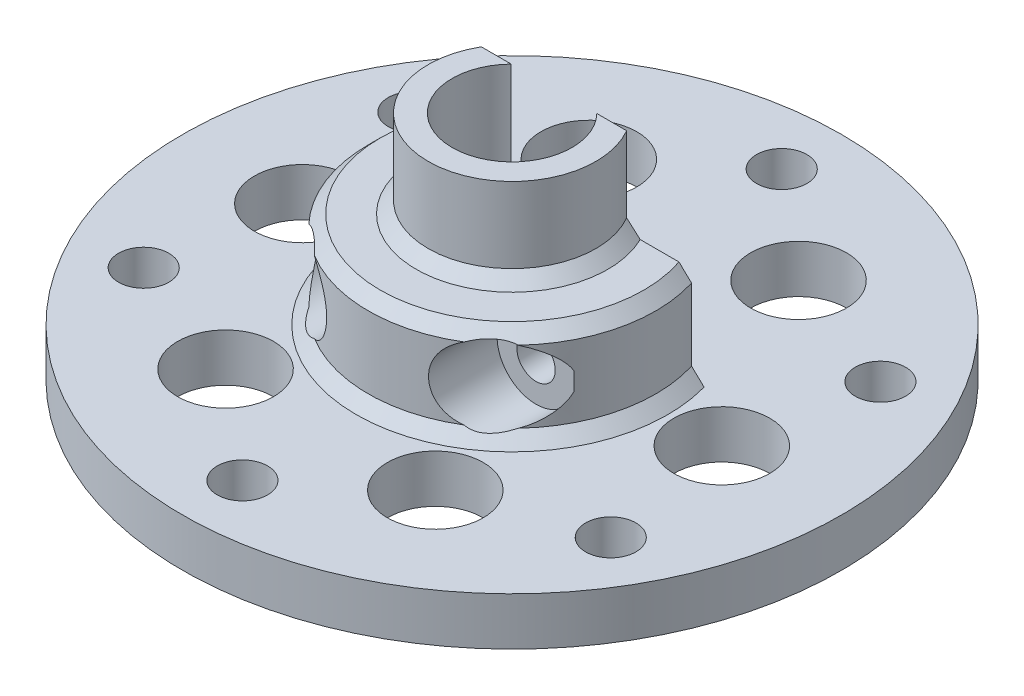
SolidWorks part; units mm, degrees
material "6061 合金"
ref_plane "前视基准面" through (0, 0, 0) normal (0, 0, 1) x (1, 0, 0)
ref_plane "上视基准面" through (0, 0, 0) normal (0, 1, 0) x (1, 0, 0)
ref_plane "右视基准面" through (0, 0, 0) normal (1, 0, 0) x (0, 0, -1)
sketch "草图1" plane through (0, 0, 0) normal (0, 0, 1) x (1, 0, 0)
  line L0 (0, 0) -> (0, 21.0564) construction
  line L1 (-5, 0) -> (-27.5, 0)
  line L2 (-27.5, 0) -> (-27.5, 4)
  line L3 (-27.5, 4) -> (-12, 4)
  line L4 (-12, 4) -> (-12, 12)
  line L5 (-12, 12) -> (-7, 12)
  line L8 (-5, 19.3) -> (-5, 0)
  line L9 (-7, 12) -> (-7, 19.3)
  line L10 (-7, 19.3) -> (-5, 19.3)
  dimension "D1" = 10
  dimension "D2" = 8
  dimension "D3" = 24
  dimension "D4" = 55
  dimension "D5" = 4
  dimension "D6" = 2
  dimension "D7" = 7.3
revolve "旋转1" add sketch "草图1" angle 360 about L0
sketch "草图2" plane through (0, 0, 0) normal (0, -1, 0) x (1, 0, 0)
  circle A7 centre (-8.75, -15.1554) radius 4
  circle A8 centre (-8.75, 15.1554) radius 4
  circle A9 centre (0, 0) radius 17.5 construction
  circle A10 centre (8.75, 15.1554) radius 4
  circle A11 centre (17.5, 0) radius 4
  circle A12 centre (8.75, -15.1554) radius 4
  circle A13 centre (-17.5, 0) radius 4
  point P1 (0, 0)
  point P15 (0, 0)
  dimension "D4" = 35
  dimension "D5" = 8
  dimension "D3" = 6
extrude "切除-拉伸2" cut sketch "草图2" against normal blind 10
sketch "草图6" plane through (0, 12, 0) normal (0, -1, 0) x (1, 0, 0)
  line L0 (11.4782, -3.5) -> (-11.4782, -3.5)
  circle A5 centre (0, 0) radius 12 construction
  arc A6 (-11.4782, -3.5) -> (11.4782, -3.5) centre (0, 0) ccw
  circle A7 centre (0, 0) radius 12 construction
  dimension "D2" = 3.5
extrude "切除-拉伸4" cut sketch "草图6" along normal up to surface and the other way through all up to face at (-17.5, 4, -4)
chamfer "倒角1" distance 1 angle 45 4 edges at (0, 4, 12) (0, 12, 12) (0, 0, -5) (0, 12, 7)
sketch "草图3" plane through (0, 0, 0) normal (0, 0, 1) x (1, 0, 0)
  line L0 (27.5, 4) -> (-27.5, 4) construction
  line L1 (0, 22.6853) -> (0, 0) construction
  line L2 (7.5, 8) -> (-7.5, 8) construction
  circle A1 centre (7.5, 8) radius 1.6
  circle A2 centre (-7.5, 8) radius 1.6
  point P2 (0, 8)
  dimension "D1" = 4
  dimension "D3" = 15
  dimension "D4" = 3.2
extrude "切除-拉伸3" cut sketch "草图3" against normal through all and the other way through all
ref_plane "基准面1" through (0, 0, 5.5) normal (0, 0, -1) x (-1, 0, 0)
sketch "草图7" plane through (0, 0, 5.5) normal (0, 0, -1) x (-1, 0, 0)
  circle A0 centre (-7.5, 8) radius 3.25
  circle A1 centre (7.5, 8) radius 3.25
  dimension "D1" = 6.5
extrude "切除-拉伸5" cut sketch "草图7" against normal through all
hole_wizard "M5 螺纹孔1" positions "草图8" profile "草图9" tap size "M5" standard "GB" end condition through all
sketch "草图8" plane through (0, 4, 0) normal (0, 1, 0) x (1, 0, 0)
  circle A0 centre (0, 0) radius 22.5 construction
  point P15 (0, 22.5)
  point P28 (19.4856, 11.25)
  point P29 (19.4856, -11.25)
  point P30 (0, -22.5)
  point P31 (-19.4856, -11.25)
  point P32 (-19.4856, 11.25)
  point P33 (0, 22.5)
  dimension "D1" = 45
  dimension "D2" = 6
sketch "草图9" plane through (0, 4, -22.5) normal (1, 0, 0) x (0, 0, 1)
  line L0 (0, 0) -> (0, 4)
  line L1 (0, 4) -> (2.1, 4)
  line L2 (2.1, 4) -> (2.1, 0)
  line L5 (2.1, 0) -> (0, 0)
  line L11 (0, -6.35) -> (0, 107.95) construction
  dimension "通孔螺纹孔钻头直径" = 4.2
  dimension "通孔螺纹孔钻头深度" = 4
cosmetic thread "孔螺蚊线1" parameters "D2"=5
cosmetic thread "孔螺蚊线2" parameters "D2"=5
cosmetic thread "孔螺蚊线3" parameters "D2"=5
cosmetic thread "孔螺蚊线4" parameters "D2"=5
cosmetic thread "孔螺蚊线5" parameters "D2"=5
cosmetic thread "孔螺蚊线6" parameters "D2"=5
